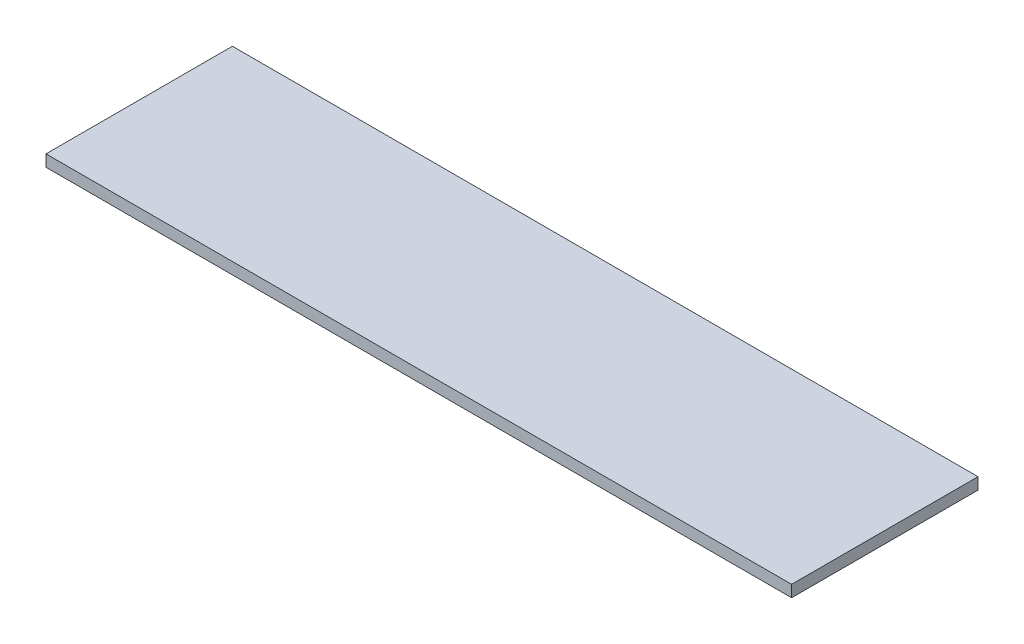
SolidWorks part; units mm, degrees
ref_plane "Front Plane" through (0, 0, 0) normal (0, 0, 1) x (1, 0, 0)
ref_plane "Top Plane" through (0, 0, 0) normal (0, 1, 0) x (1, 0, 0)
ref_plane "Right Plane" through (0, 0, 0) normal (1, 0, 0) x (0, 0, -1)
sketch "Sketch1" plane through (0, 0, 0) normal (0, 1, 0) x (1, 0, 0)
  line L1 (-609.6, 152.4) -> (609.6, 152.4)
  line L2 (-609.6, 152.4) -> (-609.6, -152.4)
  line L3 (-609.6, -152.4) -> (609.6, -152.4)
  line L4 (609.6, 152.4) -> (609.6, -152.4)
  line L5 (-609.6, 152.4) -> (609.6, -152.4) construction
  line L6 (-609.6, -152.4) -> (609.6, 152.4) construction
  point P0 (0, 0)
  dimension "D1" = 304.8
  dimension "D2" = 1219.2
extrude "Boss-Extrude1" add sketch "Sketch1" along normal blind 19.05
